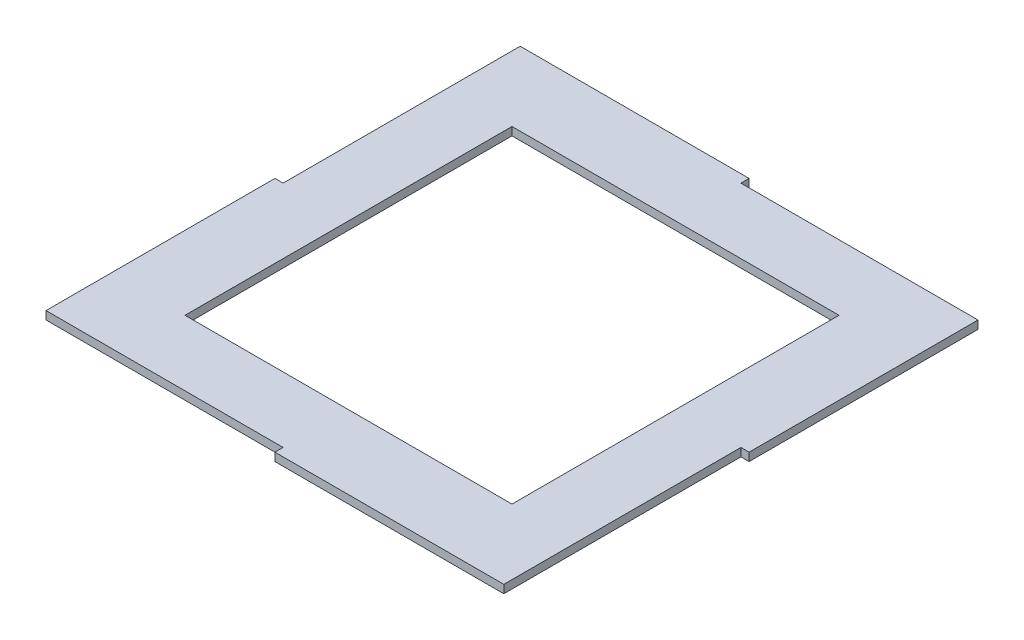
SolidWorks part; units mm, degrees
material "Acrylic (Medium-high impact)"
ref_plane "Front Plane" through (0, 0, 0) normal (0, 0, 1) x (1, 0, 0)
ref_plane "Top Plane" through (0, 0, 0) normal (0, 1, 0) x (1, 0, 0)
ref_plane "Right Plane" through (0, 0, 0) normal (1, 0, 0) x (0, 0, -1)
sketch "Sketch1" plane through (0, 0, 0) normal (0, 1, 0) x (1, 0, 0)
  line L0 (-112.5062, 93.3127) -> (-112.5062, 96.4877)
  line L1 (-112.5062, 93.3127) -> (65.2938, 93.3127)
  line L2 (-112.5062, 93.3127) -> (-112.5062, -84.4873)
  line L3 (-112.5062, -84.4873) -> (65.2938, -84.4873)
  line L4 (65.2938, 93.3127) -> (65.2938, -84.4873)
  line L5 (-112.5062, 96.4877) -> (-23.6062, 96.4877)
  line L6 (-23.6062, 96.4877) -> (-23.6062, 93.3127)
  line L7 (-112.5062, -84.4873) -> (-115.6812, -84.4873)
  line L8 (-115.6812, -84.4873) -> (-115.6812, 4.4127)
  line L9 (-115.6812, 4.4127) -> (-112.5062, 4.4127)
  line L10 (65.2938, -84.4873) -> (65.2938, -87.6623)
  line L11 (65.2938, -87.6623) -> (-23.6062, -87.6623)
  line L12 (-23.6062, -87.6623) -> (-23.6062, -84.4873)
  line L13 (65.2938, 93.3127) -> (68.4688, 93.3127)
  line L14 (68.4688, 93.3127) -> (68.4688, 4.4127)
  line L15 (68.4688, 4.4127) -> (65.2938, 4.4127)
  line L17 (39.8938, -59.0873) -> (-87.1062, -59.0873)
  line L18 (39.8938, -59.0873) -> (39.8938, 67.9127)
  line L19 (39.8938, 67.9127) -> (-87.1062, 67.9127)
  line L20 (-87.1062, -59.0873) -> (-87.1062, 67.9127)
  point P4 (-23.6062, 93.3127)
  point P5 (-112.5062, 4.4127)
  point P9 (65.2938, 4.4127)
  point P10 (-23.6062, -84.4873)
  dimension "D1" = 177.8
  dimension "D2" = 177.8
  dimension "D3" = 3.175
  dimension "D4" = 3.175
  dimension "D5" = 3.175
  dimension "D6" = 3.175
  dimension "D7" = 127
  dimension "D8" = 127
  dimension "D9" = 25.4
  dimension "D10" = 25.4
extrude "Boss-Extrude1" add sketch "Sketch1" along normal blind 3.175 contours L9 L8 L7 L2 | L6 L5 L0 L1 | L4 L1 L2 L3 | L15 L14 L13 L4 | L12 L11 L10 L3
